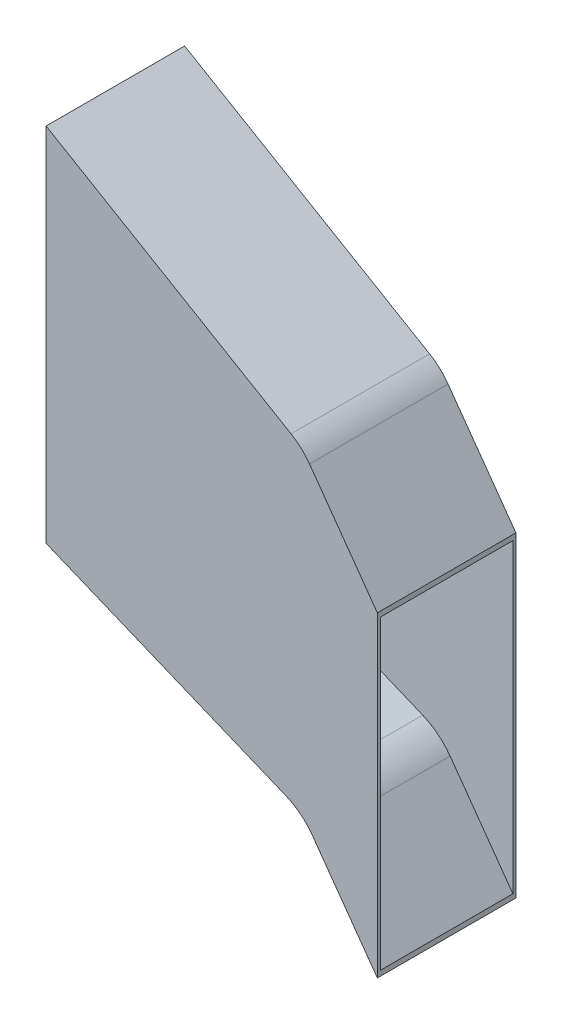
SolidWorks part; units mm, degrees
ref_plane "Front Plane" through (0, 0, 0) normal (0, 0, 1) x (1, 0, 0)
ref_plane "Top Plane" through (0, 0, 0) normal (0, 1, 0) x (1, 0, 0)
ref_plane "Right Plane" through (0, 0, 0) normal (1, 0, 0) x (0, 0, -1)
sketch "Sketch1" plane through (0, 0, 0) normal (0, 0, 1) x (1, 0, 0)
  line L0 (0, 0) -> (0, 266.7)
  line L1 (0, 266.7) -> (-63.5, 355.6)
  line L2 (-63.5, 355.6) -> (-279.4, 482.6)
  line L3 (-279.4, 482.6) -> (-279.4, 177.8)
  line L4 (-279.4, 177.8) -> (-63.5, 88.9)
  line L5 (-63.5, 88.9) -> (0, 0)
  point P5 (0, 0)
  point P8 (-76.2, 312.7149)
  point P9 (-197.344, 421.8407)
  point P10 (-292.1, 168.8316)
  dimension "D1" = 63.5
  dimension "D2" = 266.7
  dimension "D3" = 88.9
  dimension "D4" = 215.9
  dimension "D5" = 88.9
  dimension "D6" = 127
extrude "Boss-Extrude1" add sketch "Sketch1" along normal blind 116.84
fillet "Fillet1" radius 50.8 2 edges at (-63.5, 355.6, 58.42) (-63.5, 88.9, 58.42)
shell "Shell2" thickness 2.54
